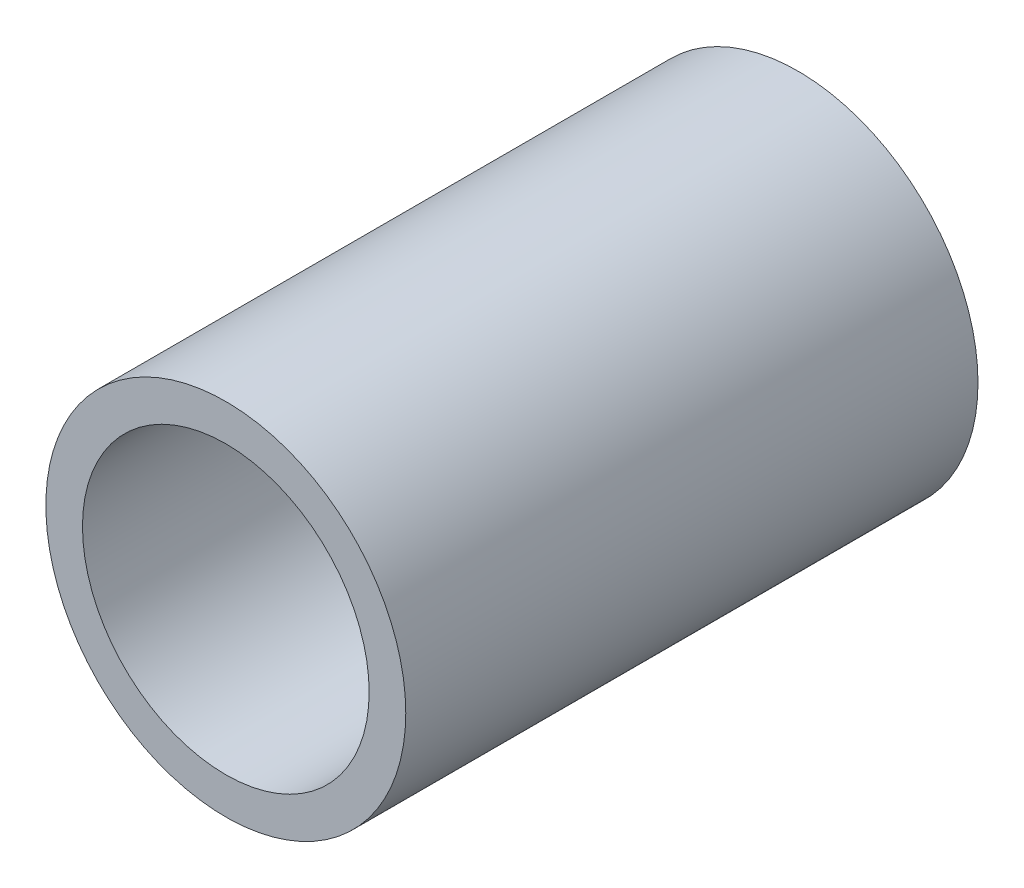
SolidWorks part; units mm, degrees
ref_plane "Front Plane" through (0, 0, 0) normal (0, 0, 1) x (1, 0, 0)
ref_plane "Top Plane" through (0, 0, 0) normal (0, 1, 0) x (1, 0, 0)
ref_plane "Right Plane" through (0, 0, 0) normal (1, 0, 0) x (0, 0, -1)
sketch "Sketch1" plane through (0, 0, 0) normal (0, 0, 1) x (1, 0, 0)
  circle A0 centre (0, 0) radius 3.9942
  circle A1 centre (0, 0) radius 3.1813
  dimension "OD" = 7.9883
  dimension "ID" = 6.3627
sketch "Sketch2" plane through (0, 0, 0) normal (1, 0, 0) x (0, 0, -1)
  line L2 (6.35, 0) -> (-6.35, 0) construction
  line L4 (-6.35, -3.9942) -> (-6.35, 3.9941) construction
  line L5 (-6.35, -3.1813) -> (6.35, -3.1813)
  line L6 (6.35, 3.1813) -> (-6.35, 3.1813)
  line L7 (6.35, -3.9941) -> (6.35, 3.9941) construction
  line L8 (-6.35, 3.9941) -> (6.35, 3.9941) construction
  line L9 (-6.35, -3.9942) -> (6.35, -3.9941) construction
  line L10 (0, 3.9942) -> (0, -3.9942) construction
  line L11 (0, 3.1813) -> (0, -3.1813) construction
  point P4 (0, -3.1813)
  point P7 (0, 3.1813)
  point P8 (0, 0)
  point P12 (-6.35, 0)
  point P15 (6.35, 0)
  point P16 (0, -3.9942)
  point P17 (0, 3.9942)
  dimension "Length" = 12.7
sketch "Sketch5" plane through (0, 0, 0) normal (0, 0, 1) x (1, 0, 0)
  circle A1 centre (0, 0) radius 3.1813
  circle A2 centre (0, 0) radius 3.1813
  circle A3 centre (0, 0) radius 3.9942
  circle A4 centre (0, 0) radius 3.9942
  dimension "D1" = 0
  dimension "D2" = 0
extrude "Boss-Extrude1" add sketch "Sketch5" along normal up to vertex (6.35 mm away) and the other way up to vertex (6.35 mm away) up to point (0, 0, 6.35) other way up to point (0, 0, -6.35)
sketch "Sketch4" plane through (0, 0, 6.35) normal (0, 0, 1) x (1, 0, 0)
  line L0 (0, 0) -> (-2.2496, 2.2496)
  line L2 (0, -3.9942) -> (0, 3.9941) construction
  circle A1 centre (0, 0) radius 3.1813 construction
  dimension "D1" = 45
equation "\"D1\"= \"Length@Sketch2\""
